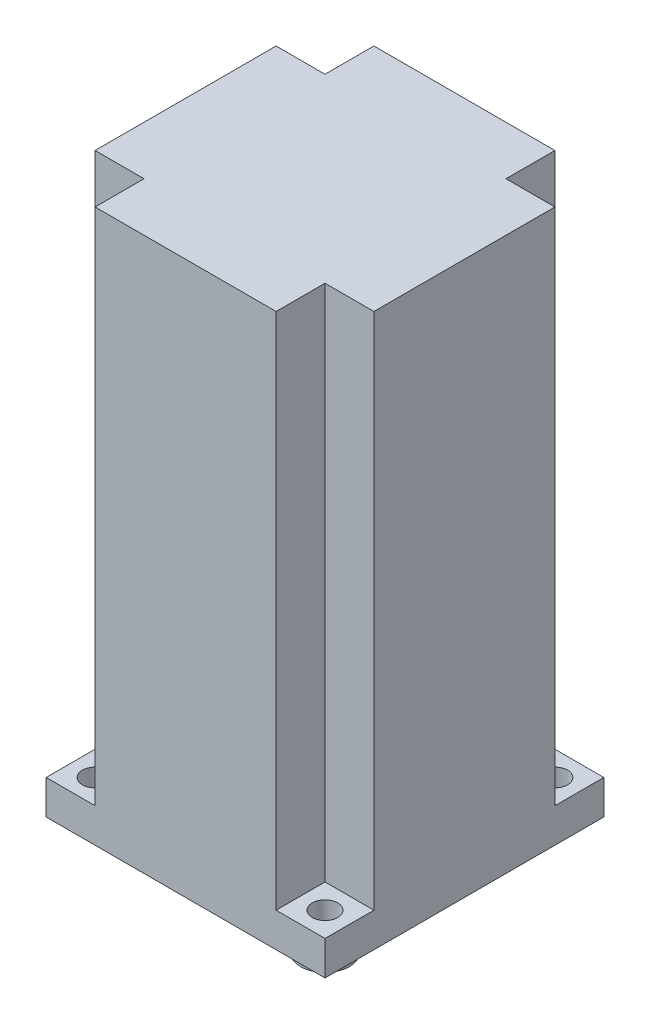
SolidWorks part; units mm, degrees
ref_plane "Alzado" through (0, 0, 0) normal (0, 0, 1) x (1, 0, 0)
ref_plane "Planta" through (0, 0, 0) normal (0, 1, 0) x (1, 0, 0)
ref_plane "Vista lateral" through (0, 0, 0) normal (1, 0, 0) x (0, 0, -1)
sketch "Croquis1" plane through (0, 0, 0) normal (0, 1, 0) x (1, 0, 0)
  line L1 (28.5, 28.5) -> (-28.5, 28.5)
  line L2 (28.5, 28.5) -> (28.5, -28.5)
  line L3 (28.5, -28.5) -> (-28.5, -28.5)
  line L4 (-28.5, 28.5) -> (-28.5, -28.5)
  line L5 (28.5, 28.5) -> (-28.5, -28.5) construction
  line L6 (28.5, -28.5) -> (-28.5, 28.5) construction
  point P0 (0, 0)
  dimension "D1" = 57
  dimension "D2" = 57
extrude "Saliente-Extruir1" add sketch "Croquis1" along normal blind 113
sketch "Croquis2" plane through (0, 0, 0) normal (0, -1, 0) x (-1, 0, 0)
  circle A0 centre (0, 0) radius 5
  dimension "D1" = 10
extrude "Saliente-Extruir2" add sketch "Croquis2" along normal blind 24
hole_wizard "Taladro de margen para M51" positions "Croquis4" profile "Croquis5" hole size "M5" standard "Ansi Metric" end condition up to next
sketch "Croquis4" plane through (0, 0, 0) normal (0, -1, 0) x (-1, 0, 0)
  line L0 (23.5, -23.5) -> (-23.5, -23.5) construction
  point P0 (23.5, -23.5)
  point P9 (-23.5, -23.5)
  point P10 (-23.5, 23.5)
  point P11 (23.5, 23.5)
  dimension "D1" = 47
  dimension "D2" = 4
sketch "Croquis5" plane through (-23.5, 0, 23.5) normal (1, 0, 0) x (0, 0, -1)
  line L0 (0, 0) -> (0, 113)
  line L1 (0, 113) -> (2.6, 113)
  line L2 (2.6, 113) -> (2.6, 0)
  line L5 (2.6, 0) -> (0, 0)
  line L11 (0, -6.35) -> (0, 107.95) construction
  dimension "Diámetro de taladro hasta el siguiente" = 5.2
  dimension "Profundidad de taladro hasta el siguiente" = 113
sketch "Croquis8" plane through (0, 113, 0) normal (0, 1, 0) x (1, 0, 0)
  line L1 (28.5, 28.5) -> (18.5, 28.5)
  line L2 (28.5, 28.5) -> (28.5, 18.5)
  line L3 (28.5, 18.5) -> (18.5, 18.5)
  line L4 (18.5, 28.5) -> (18.5, 18.5)
  line L5 (28.5, -28.5) -> (18.5, -28.5)
  line L6 (28.5, -28.5) -> (28.5, -18.5)
  line L7 (28.5, -18.5) -> (18.5, -18.5)
  line L8 (18.5, -28.5) -> (18.5, -18.5)
  line L9 (-28.5, 28.5) -> (-18.5, 28.5)
  line L10 (-28.5, 28.5) -> (-28.5, 18.5)
  line L11 (-28.5, 18.5) -> (-18.5, 18.5)
  line L12 (-18.5, 28.5) -> (-18.5, 18.5)
  line L13 (-28.5, -28.5) -> (-18.5, -28.5)
  line L14 (-28.5, -28.5) -> (-28.5, -18.5)
  line L15 (-28.5, -18.5) -> (-18.5, -18.5)
  line L16 (-18.5, -28.5) -> (-18.5, -18.5)
  circle M9 centre (-23.5, -23.5) radius 2.6
  circle M10 centre (23.5, -23.5) radius 2.6
  circle M12 centre (-23.5, 23.5) radius 2.6
  line M13 (-28.5, 28.5) -> (-28.5, -28.5)
  line M14 (-28.5, -28.5) -> (28.5, -28.5)
  line M15 (28.5, -28.5) -> (28.5, 28.5)
  line M16 (28.5, 28.5) -> (-28.5, 28.5)
  dimension "D1" = 10
  dimension "D2" = 10
  dimension "D3" = 10
  dimension "D4" = 10
extrude "Cortar-Extruir1" cut sketch "Croquis8" against normal blind 106 contours M12 | M10 | L16 L15 M14 M13 M9 | L8 L7 M14 M15 M10 | L12 L11 M16 M13 M12 | L4 L3 L2 L1
